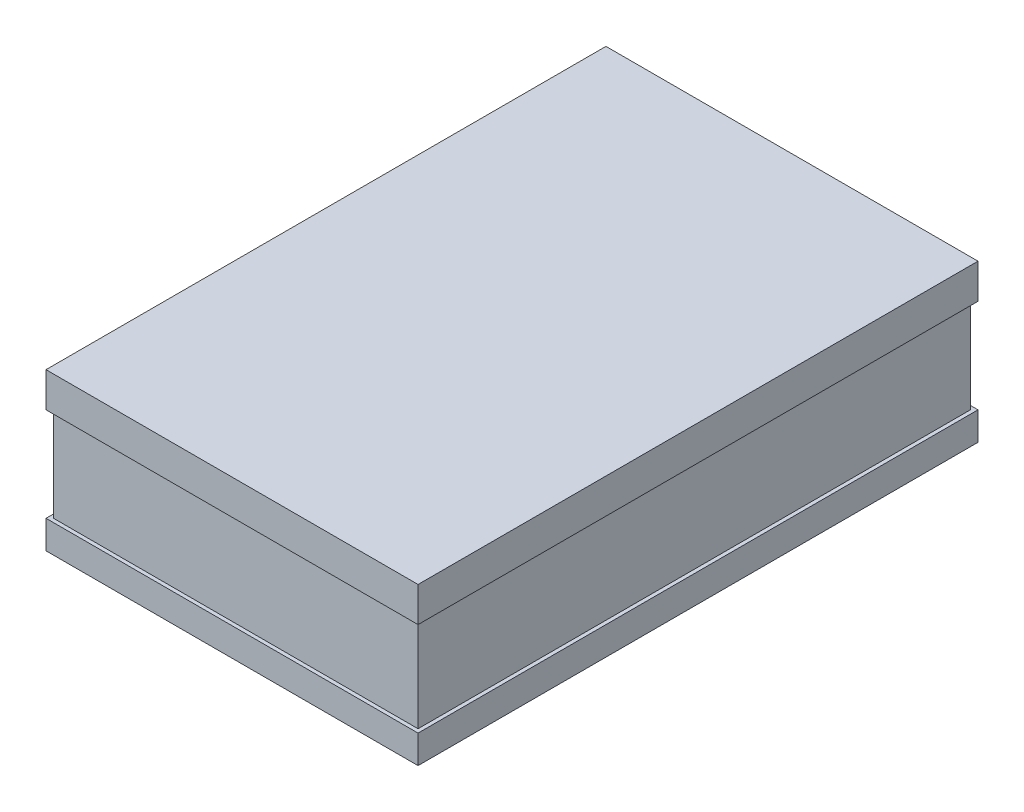
SolidWorks part; units mm, degrees
ref_plane "前视基准面" through (0, 0, 0) normal (0, 0, 1) x (1, 0, 0)
ref_plane "上视基准面" through (0, 0, 0) normal (0, 1, 0) x (1, 0, 0)
ref_plane "右视基准面" through (0, 0, 0) normal (1, 0, 0) x (0, 0, -1)
sketch "草图1" plane through (0, 0, 0) normal (0, 1, 0) x (1, 0, 0)
  line L0 (-99, -149) -> (99, -149)
  line L1 (-99, -149) -> (-99, 149)
  line L2 (99, -149) -> (99, 149)
  line L3 (-99, 149) -> (99, 149)
  line L4 (-99, -149) -> (99, 149) construction
  line L5 (99, -149) -> (-99, 149) construction
  line L6 (-87.5, -137.5) -> (-87.5, 137.5)
  line L7 (-87.5, 137.5) -> (87.5, 137.5)
  line L8 (87.5, -137.5) -> (87.5, 137.5)
  line L9 (-87.5, -137.5) -> (87.5, -137.5)
  point P1 (0, 0)
  dimension "D1" = 198
  dimension "D2" = 298
  dimension "D3" = 11.5
extrude "凸台-拉伸1" add sketch "草图1" against normal blind 80
sketch "草图2" plane through (0, 0, 0) normal (0, 1, 0) x (1, 0, 0)
  line L5 (-99, 149) -> (99, 149)
  line L6 (-99, 149) -> (-99, -149)
  line L7 (-99, -149) -> (99, -149)
  line L8 (99, 149) -> (99, -149)
extrude "凸台-拉伸2" add sketch "草图2" along normal blind 3.5
ref_plane "基准面1" through (0, -40, 0) normal (0, -1, 0) x (-1, 0, 0)
sketch "草图3" plane through (0, -40, 0) normal (0, -1, 0) x (-1, 0, 0)
  line L0 (97, 147) -> (-97, 147)
  line L5 (97, 147) -> (97, -147)
  line L6 (-97, 147) -> (-97, -147)
  line L7 (97, -147) -> (-97, -147)
  line L8 (97, 147) -> (-97, -147) construction
  line L9 (-97, 147) -> (97, -147) construction
  line L10 (100, -150) -> (-100, -150)
  line L11 (-100, 150) -> (-100, -150)
  line L12 (100, 150) -> (-100, 150)
  line L13 (100, 150) -> (100, -150)
  point P1 (0, 0)
  dimension "D1" = 194
  dimension "D2" = 294
  dimension "D3" = 3
extrude "切除-拉伸1" cut sketch "草图3" against normal mid plane 50
